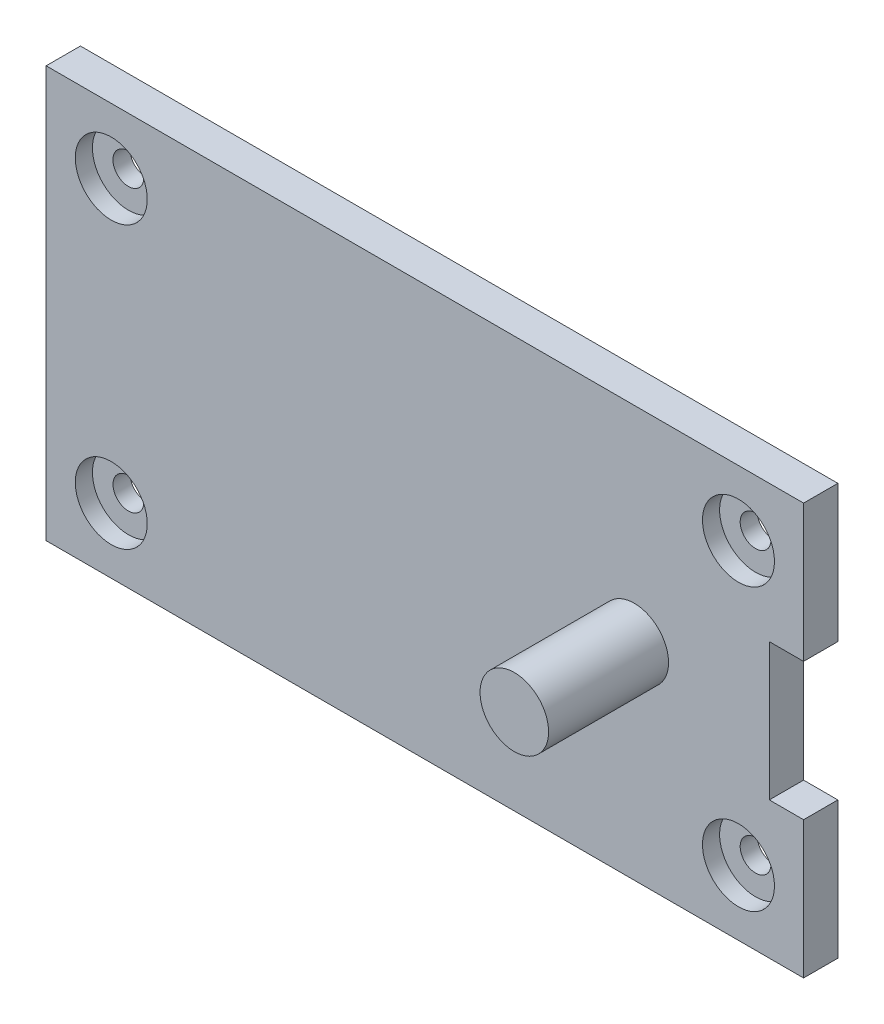
SolidWorks part; units mm, degrees
ref_plane "Front Plane" through (0, 0, 0) normal (0, 0, 1) x (1, 0, 0)
ref_plane "Top Plane" through (0, 0, 0) normal (0, 1, 0) x (1, 0, 0)
ref_plane "Right Plane" through (0, 0, 0) normal (1, 0, 0) x (0, 0, -1)
sketch "Sketch1" plane through (0, 0, 0) normal (0, 0, 1) x (1, 0, 0)
  line L1 (0, 0) -> (40.2, 0)
  line L2 (0, 0) -> (0, 20)
  line L3 (0, 20) -> (40.2, 20)
  line L4 (40.2, 0) -> (40.2, 20)
  line L5 (-2, 22) -> (42.2, 22)
  line L6 (-2, 22) -> (-2, -2)
  line L7 (-2, -2) -> (42.2, -2)
  line L8 (42.2, 22) -> (42.2, -2)
  dimension "D1" = 40.2
  dimension "D2" = 20
  dimension "D3" = 2
  dimension "D4" = 2
  dimension "D5" = 2
  dimension "D6" = 2
extrude "Boss-Extrude1" add sketch "Sketch1" along normal blind 11
sketch "Sketch2" plane through (0, 0, 11) normal (0, 0, 1) x (1, 0, 0)
  line L1 (-2, 22) -> (42.2, 22)
  line L2 (-2, 22) -> (-2, -2)
  line L3 (-2, -2) -> (42.2, -2)
  line L4 (42.2, 22) -> (42.2, -2)
extrude "Boss-Extrude2" add sketch "Sketch2" along normal blind 2
sketch "Sketch3" plane through (42.2, 0, 0) normal (1, 0, 0) x (0, 0, -1)
  line L0 (-13, -2) -> (-13, 22) construction
  line L1 (-13, 22) -> (0, 22) construction
  line L3 (-13, 14) -> (-2, 14)
  line L4 (-13, 14) -> (-13, 6)
  line L5 (-13, 6) -> (-2, 6)
  line L6 (-2, 14) -> (-2, 6)
  point P0 (-13, 14)
  point P1 (-12.9629, 6)
  dimension "D1" = 8
  dimension "D2" = 8
  dimension "D3" = 11
extrude "Cut-Extrude1" cut sketch "Sketch3" against normal blind 2
sketch "Sketch4" plane through (0, 0, 13) normal (0, 0, 1) x (1, 0, 0)
  line L0 (42.2, 6) -> (42.2, 14) construction
  circle A0 centre (32.32, 10) radius 2
  point P0 (32.32, 10)
  point P1 (42.2, 10)
  dimension "D1" = 9.88
extrude "Boss-Extrude3" add sketch "Sketch4" along normal blind 7
sketch "Sketch5" plane through (0, 0, 11) normal (0, 0, -1) x (-1, 0, 0)
  circle A0 centre (-38.4, 18.2) radius 0.9
  circle A1 centre (-1.8, 18.2) radius 0.9
  circle A2 centre (-1.8, 1.8) radius 0.9
  circle A3 centre (-38.4, 1.8) radius 0.9
extrude "Cut-Extrude2" cut sketch "Sketch5" against normal blind 10
sketch "Sketch6" plane through (0, 22, 0) normal (0, 1, 0) x (1, 0, 0)
  line L0 (42.2, -13) -> (42.2, 0) construction
  line L1 (-2, 0) -> (42.2, 0)
  line L2 (-2, 0) -> (-2, -11)
  line L3 (-2, -11) -> (42.2, -11)
  line L4 (42.2, 0) -> (42.2, -11)
  line L5 (42.2, -13) -> (-2, -13) construction
  dimension "D1" = 2
extrude "Cut-Extrude3" cut sketch "Sketch6" against normal blind 100
sketch "Sketch7" plane through (0, 0, 13) normal (0, 0, 1) x (1, 0, 0)
  circle A0 centre (1.8, 18.2) radius 2.1
  circle A1 centre (38.4, 18.2) radius 2.1
  circle A2 centre (38.4, 1.8) radius 2.1
  circle A3 centre (1.8, 1.8) radius 2.1
extrude "Cut-Extrude4" cut sketch "Sketch7" against normal blind 1
